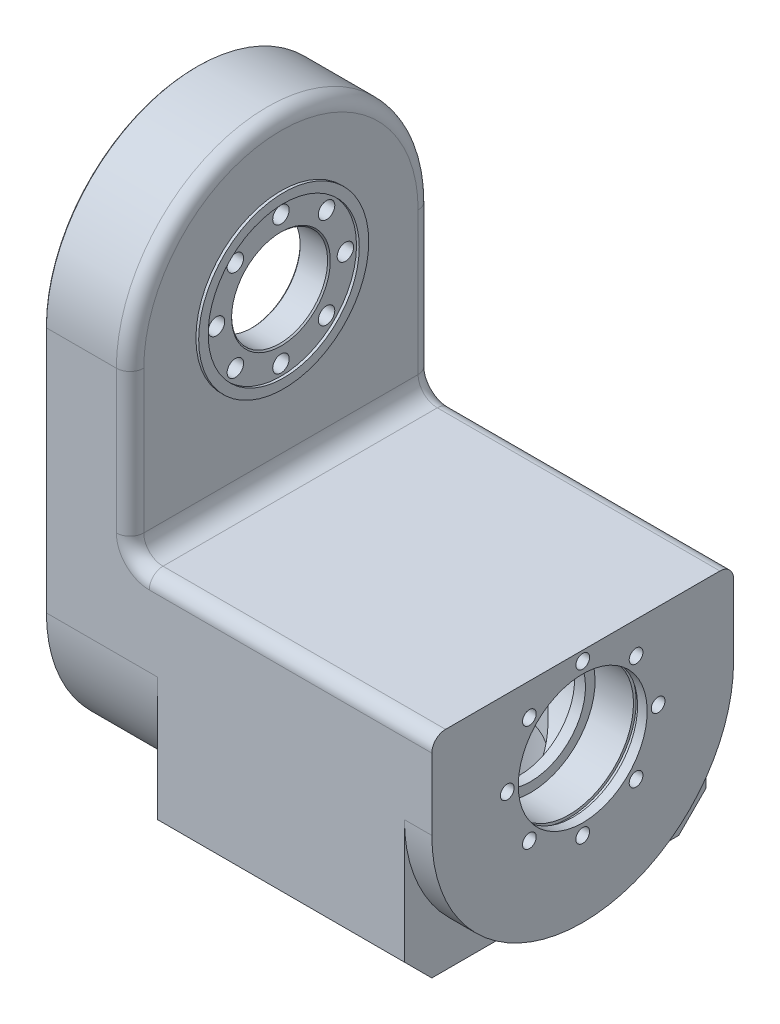
SolidWorks part; units mm, degrees
ref_plane "前视基准面" through (0, 0, 0) normal (0, 0, 1) x (1, 0, 0)
ref_plane "上视基准面" through (0, 0, 0) normal (0, 1, 0) x (1, 0, 0)
ref_plane "右视基准面" through (0, 0, 0) normal (1, 0, 0) x (0, 0, -1)
other "Configuration Table"
sketch "草图1" plane through (0, 0, 0) normal (1, 0, 0) x (0, 0, -1)
  line L0 (0, 45) -> (0, -45) construction
  line L1 (55, 45) -> (55, -45)
  line L2 (-55, 45) -> (-55, -45)
  arc A0 (55, 45) -> (-55, 45) centre (0, 45) ccw
  arc A1 (-55, -45) -> (55, -45) centre (0, -45) ccw
  point P2 (0, 0)
  dimension "D1" = 55
  dimension "D2" = 90
extrude "凸台-拉伸1" add sketch "草图1" along normal blind 41
sketch "草图2" plane through (41, 0, 0) normal (1, 0, 0) x (0, 0, -1)
  line L0 (55, -45) -> (55, 45) construction
  line L1 (-55, -14) -> (55, -14)
  line L2 (-55, -14) -> (-55, -90)
  line L3 (-45, -100) -> (45, -100)
  line L4 (55, -14) -> (55, -90)
  line L5 (-55, -14) -> (55, -100) construction
  line L6 (-55, -100) -> (55, -14) construction
  line L7 (-55, 45) -> (-55, -45) construction
  line L8 (-55, -90) -> (-45, -100)
  line L9 (45, -100) -> (55, -90)
  arc A0 (-55, -45) -> (55, -45) centre (0, -45) ccw construction
  point P0 (0, -57)
  point P5 (0, -68.9877)
  dimension "D1" = 86
extrude "凸台-拉伸2" add sketch "草图2" along normal blind 90
sketch "草图3" plane through (131, 0, 0) normal (1, 0, 0) x (0, 0, -1)
  line L0 (55, -14) -> (-55, -14) construction
  line L1 (55, -90) -> (55, -14) construction
  line L2 (-55, -14) -> (-55, -90) construction
  line L3 (55, -14) -> (-55, -14)
  line L4 (55, -45) -> (55, -14)
  line L5 (-55, -14) -> (-55, -45)
  arc A0 (0, -100) -> (55, -45) centre (0, -45) ccw construction
  arc A1 (-55, -45) -> (0, -100) centre (0, -45) ccw construction
  arc A2 (0, -100) -> (55, -45) centre (0, -45) ccw
  arc A3 (-55, -45) -> (0, -100) centre (0, -45) ccw
extrude "凸台-拉伸3" add sketch "草图3" along normal blind 10
sketch "草图4" plane through (0, 0, 0) normal (0, 0, 1) x (1, 0, 0)
  line L0 (41, 100) -> (41, -14)
  line L1 (41, -14) -> (31, -14)
  line L2 (31, -14) -> (31, 100)
  line L4 (31, 100) -> (41, 100)
  line L5 (0, 100) -> (0, 45) construction
  point P8 (0, 0)
  dimension "D1" = 31
extrude "切除-拉伸1" cut sketch "草图4" against normal through all both and the other way through all
sketch "草图5" plane through (31, 0, 0) normal (1, 0, 0) x (0, 0, -1)
  circle A0 centre (0, 45) radius 31
  circle A1 centre (0, 45) radius 27.55
  dimension "D1" = 55.1
  dimension "D2" = 62
extrude "凸台-拉伸4" add sketch "草图5" along normal blind 1
sketch "草图6" plane through (0, 0, 0) normal (-1, 0, 0) x (0, 0, 1)
  line L0 (0, 45) -> (0, -45) construction
  line L1 (47.75, 45) -> (47.75, -45)
  line L2 (-47.75, 45) -> (-47.75, -45)
  arc A0 (47.75, 45) -> (-47.75, 45) centre (0, 45) ccw
  arc A1 (-47.75, -45) -> (47.75, -45) centre (0, -45) ccw
  point P2 (0, 0)
  dimension "D1" = 95.5
  dimension "D2" = 90
extrude "切除-拉伸2" cut sketch "草图6" against normal blind 20
sketch "草图7" plane through (0, 0, 0) normal (-1, 0, 0) x (0, 0, 1)
  line L0 (0, 45) -> (0, -45) construction
  line L1 (51, 45) -> (51, -45) construction
  line L2 (-51, 45) -> (-51, -45) construction
  line L5 (0, 0) -> (55, 0) construction
  line L6 (55, 45) -> (55, -45) construction
  arc A0 (51, 45) -> (-51, 45) centre (0, 45) ccw construction
  arc A1 (-51, -45) -> (51, -45) centre (0, -45) ccw construction
  circle A6 centre (0, 96) radius 2
  circle A7 centre (-51, 45) radius 2
  circle A8 centre (51, 45) radius 2
  circle A9 centre (51, -45) radius 2
  circle A10 centre (-51, -45) radius 2
  circle A11 centre (0, -96) radius 2
  point P2 (0, 0)
  dimension "D2" = 192
  dimension "D3" = 4
  dimension "D1" = 102
extrude "切除-拉伸3" cut sketch "草图7" against normal blind 12
sketch "草图8" plane through (0, 0, -55) normal (0, 0, -1) x (-1, 0, 0)
  line L0 (0, -45) -> (0, 45) construction
  line L1 (-31, 45) -> (0, 45) construction
  circle A0 centre (-10, 0) radius 5
  dimension "D3" = 10
  dimension "D1" = 10
  dimension "D2" = 45
extrude "切除-拉伸4" cut sketch "草图8" against normal up to next
sketch "草图10" plane through (20, 0, 0) normal (-1, 0, 0) x (0, 0, 1)
  circle A0 centre (0, 45) radius 17.5
  circle A1 centre (0, 45) radius 23.5 construction
  dimension "D1" = 35
  dimension "D2" = 47
extrude "切除-拉伸5" cut sketch "草图10" against normal through all
hole_wizard "M1.6 六角头螺栓的柱形沉头孔1" positions "草图11" profile "草图12" counterbore size "M1.6" standard "GB"
sketch "草图11" plane through (20, 0, 0) normal (-1, 0, 0) x (0, 0, 1)
  circle A0 centre (0, 45) radius 23.5 construction
  point P0 (0, 68.5)
sketch "草图12" plane through (20, 68.5, 0) normal (0, 1, 0) x (0, 0, 1)
  line L0 (0, 0) -> (0, 16.8026)
  line L1 (0, 16.8026) -> (3, 15)
  line L2 (3, 15) -> (3, 6)
  line L3 (3, 6) -> (5, 6)
  line L4 (5, 6) -> (5, 0)
  line L5 (5, 0) -> (0, 0)
  line L10 (0, 16.8026) -> (-3, 15) construction
  line L11 (0, -6.35) -> (0, 107.95) construction
  dimension "孔直径" = 6
  dimension "孔深度" = 15
  dimension "柱形沉头孔直径" = 10
  dimension "柱形沉头孔深度" = 6
  dimension "导头角度" = 118
pattern_circular "阵列(圆周)1" count 8 over 360 about axis through (0, 45, 0) along (1, 0, 0) of "M1.6 六角头螺栓的柱形沉头孔1"
sketch "草图13" plane through (0, 0, 0) normal (0, 0, 1) x (1, 0, 0)
  line L0 (20, -45) -> (167.0839, -45) construction
  line L1 (20, -45) -> (20, -14)
  line L3 (20, -14) -> (30, -14)
  line L4 (30, -14) -> (30, -17.5)
  line L5 (30, -17.5) -> (118, -17.5)
  line L7 (118, -17.5) -> (118, -25)
  line L8 (118, -25) -> (122, -25)
  line L9 (122, -25) -> (122, -21.5)
  line L10 (122, -21.5) -> (136, -21.5)
  line L11 (136, -21.5) -> (136, -20.5)
  line L12 (136, -20.5) -> (137.5, -20.5)
  line L13 (137.5, -20.5) -> (137.5, -21.5)
  line L14 (137.5, -21.5) -> (141, -21.5)
  line L16 (141, -21.5) -> (141, -45)
  line L17 (141, -45) -> (20, -45)
  line L18 (20, -45) -> (20, 45) construction
  line L19 (0, 45) -> (0, -45) construction
  line L20 (141, -14) -> (141, -45) construction
  dimension "D1" = 62
  dimension "D2" = 55
  dimension "D3" = 10
  dimension "D4" = 40
  dimension "D5" = 47
  dimension "D6" = 49
  dimension "D7" = 118
  dimension "D8" = 19
  dimension "D9" = 3.5
  dimension "D10" = 5
revolve "切除-旋转1" cut sketch "草图13" angle 360 about L0
sketch "草图14" plane through (141, 0, 0) normal (1, 0, 0) x (0, 0, -1)
  circle A0 centre (0, -45) radius 27.5 construction
  circle A1 centre (0, -17.5) radius 2.5
  circle A2 centre (19.4454, -25.5546) radius 2.5
  circle A3 centre (27.5, -45) radius 2.5
  circle A4 centre (19.4454, -64.4454) radius 2.5
  circle A5 centre (0, -72.5) radius 2.5
  circle A6 centre (-19.4454, -64.4454) radius 2.5
  circle A7 centre (-27.5, -45) radius 2.5
  circle A8 centre (-19.4454, -25.5546) radius 2.5
  point P6 (0, -45)
  point P21 (0, -45)
  dimension "D1" = 55
  dimension "D2" = 5
  dimension "D3" = 8
extrude "切除-拉伸6" cut sketch "草图14" against normal blind 15
sketch "草图15" plane through (0, -100, 0) normal (0, -1, 0) x (1, 0, 0)
  line L0 (131, 45) -> (41, 45) construction
  circle A0 centre (86, 0) radius 34
  point P4 (86, 45)
  point P5 (0, 0)
  dimension "D1" = 68
extrude "切除-拉伸7" cut sketch "草图15" against normal blind 25
sketch "草图16" plane through (0, -75, 0) normal (0, -1, 0) x (1, 0, 0)
  circle A0 centre (86, 0) radius 30
  dimension "D1" = 60
extrude "切除-拉伸8" cut sketch "草图16" against normal blind 25
sketch "草图17" plane through (0, -100, 0) normal (0, -1, 0) x (1, 0, 0)
  circle A0 centre (86, 0) radius 40 construction
  circle A1 centre (86, 40) radius 2.5
  circle A2 centre (114.2843, 28.2843) radius 2.5
  circle A3 centre (126, 0) radius 2.5
  circle A4 centre (114.2843, -28.2843) radius 2.5
  circle A5 centre (86, -40) radius 2.5
  circle A6 centre (57.7157, -28.2843) radius 2.5
  circle A7 centre (46, 0) radius 2.5
  circle A8 centre (57.7157, 28.2843) radius 2.5
  point P5 (126, 0)
  point P22 (86, 0)
  dimension "D1" = 80
  dimension "D2" = 5
  dimension "D3" = 8
extrude "切除-拉伸9" cut sketch "草图17" against normal blind 15
sketch "草图18" plane through (0, 0, -55) normal (0, 0, -1) x (-1, 0, 0)
  line L1 (-32, 76) -> (-32, 14) construction
  line L2 (-141, -45) -> (-131, -45) construction
  point P0 (-86, -45)
  dimension "D1" = 54
hole_wizard "M1.6 六角头螺栓的柱形沉头孔2" positions "草图19" profile "草图20" counterbore size "M1.6" standard "GB"
sketch "草图19" plane through (0, 0, -55) normal (0, 0, -1) x (-1, 0, 0)
  point P0 (-86, -45)
sketch "草图20" plane through (86, -45, -55) normal (1, 0, 0) x (0, 1, 0)
  line L0 (0, 0) -> (0, 31.2017)
  line L1 (0, 31.2017) -> (2, 30)
  line L2 (2, 30) -> (2, 12)
  line L3 (2, 12) -> (5, 12)
  line L4 (5, 12) -> (5, 0)
  line L5 (5, 0) -> (0, 0)
  line L10 (0, 31.2017) -> (-2, 30) construction
  line L11 (0, -6.35) -> (0, 107.95) construction
  dimension "孔直径" = 4
  dimension "孔深度" = 30
  dimension "柱形沉头孔直径" = 10
  dimension "柱形沉头孔深度" = 12
  dimension "导头角度" = 118
fillet "圆角2" radius 7 1 edges at (31, -14, 0)
fillet "圆角1" radius 5 7 edges at (31, 19, 55) (31, 100, 0) (89.5, -14, -55) (89.5, -14, 55) (31, 19, -55) (33.0503, -11.9497, 55) (33.0503, -11.9497, -55)
chamfer "倒角1" distance 0.5 angle 45 8 edges at (20, -76, 0) (20, 45, 17.5) (31, 45, 17.5) (86, -100, -34) (0, 100, 0) (0, 0, 55) (0, 0, -55) (0, -100, 0)
